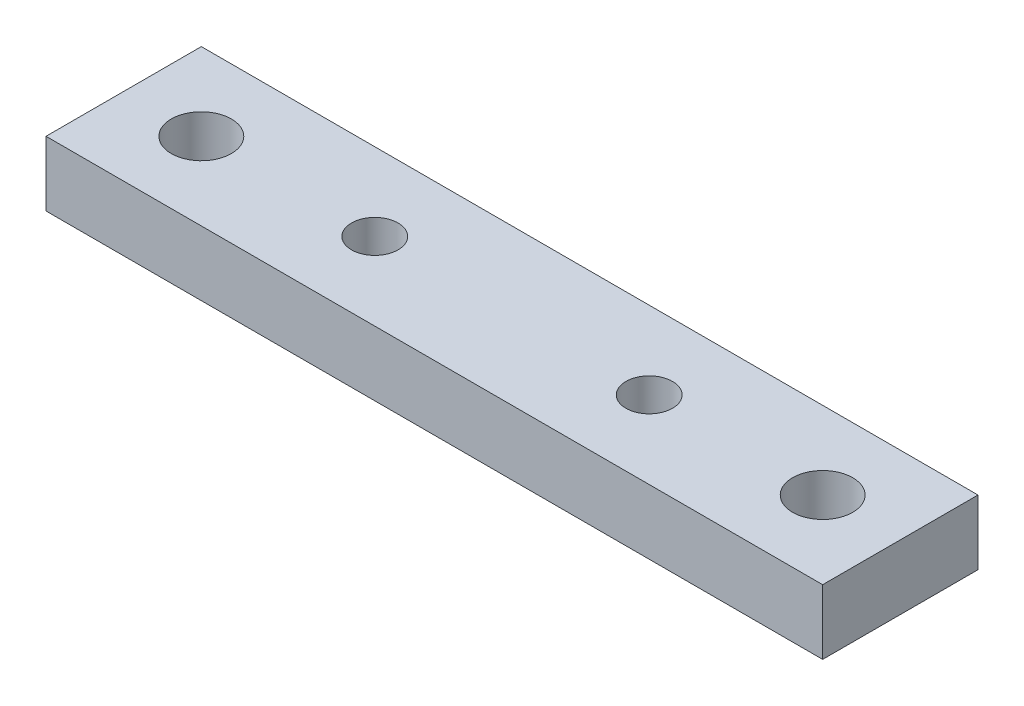
SolidWorks part; units mm, degrees
ref_plane "Front Plane" through (0, 0, 0) normal (0, 0, 1) x (1, 0, 0)
ref_plane "Top Plane" through (0, 0, 0) normal (0, 1, 0) x (1, 0, 0)
ref_plane "Right Plane" through (0, 0, 0) normal (1, 0, 0) x (0, 0, -1)
sketch "Sketch1" plane through (0, 0, 0) normal (0, 1, 0) x (1, 0, 0)
  line L0 (0, 3.81) -> (0, -3.81) construction
  line L1 (-19.05, 3.81) -> (19.05, 3.81)
  line L2 (-19.05, 3.81) -> (-19.05, -3.81)
  line L3 (-19.05, -3.81) -> (19.05, -3.81)
  line L4 (19.05, 3.81) -> (19.05, -3.81)
  line L5 (-19.05, 0) -> (19.05, 0) construction
  circle A0 centre (-15.24, 0) radius 1.4732
  circle A1 centre (-6.731, 0) radius 1.143
  circle A2 centre (15.24, 0) radius 1.4732
  circle A3 centre (6.731, 0) radius 1.143
  point P0 (0, 0)
  dimension "D2" = 2.9464
  dimension "D3" = 15.24
  dimension "D4" = 2.286
  dimension "D5" = 6.731
  dimension "D1" = 38.1
  dimension "D6" = 7.62
extrude "Boss-Extrude1" add sketch "Sketch1" along normal blind 3.175
